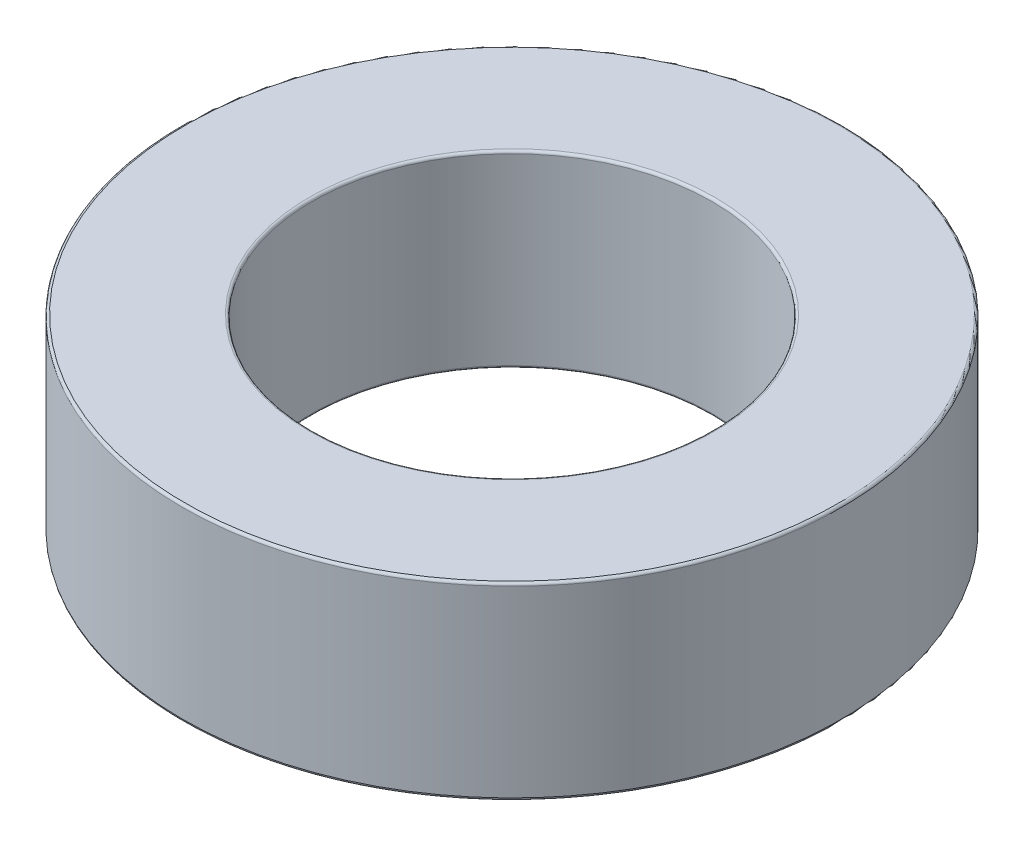
SolidWorks part; units mm, degrees
ref_plane "Front Plane" through (0, 0, 0) normal (0, 0, 1) x (1, 0, 0)
ref_plane "Top Plane" through (0, 0, 0) normal (0, 1, 0) x (1, 0, 0)
ref_plane "Right Plane" through (0, 0, 0) normal (1, 0, 0) x (0, 0, -1)
sketch "Toroidal Core" plane through (0, 0, 0) normal (0, 0, 1) x (1, 0, 0)
  line L0 (0, -8.108) -> (0, 13.3131) construction
  line L2 (11.5974, 0) -> (18.7136, 0)
  line L3 (11.4513, 0.1461) -> (11.4513, 10.6401)
  line L4 (11.5974, 10.7862) -> (18.7136, 10.7862)
  line L5 (18.8597, 0.1461) -> (18.8597, 10.6401)
  arc A0 (11.5974, 0) -> (11.4513, 0.1461) centre (11.5974, 0.1461) cw
  arc A1 (18.7136, 0) -> (18.8597, 0.1461) centre (18.7136, 0.1461) ccw
  arc A2 (18.7136, 10.7862) -> (18.8597, 10.6401) centre (18.7136, 10.6401) cw
  arc A3 (11.4513, 10.6401) -> (11.5974, 10.7862) centre (11.5974, 10.6401) cw
  point P9 (11.4513, 0)
  point P12 (18.8597, 0)
  point P15 (18.8597, 10.7862)
  point P18 (11.4513, 10.7862)
  dimension "D4" = 0.1461
  dimension "D1" = 7.4084
  dimension "D2" = 10.7862
  dimension "D3" = 11.4513
revolve "Revolve2" add sketch "Toroidal Core" angle 360 about L0
